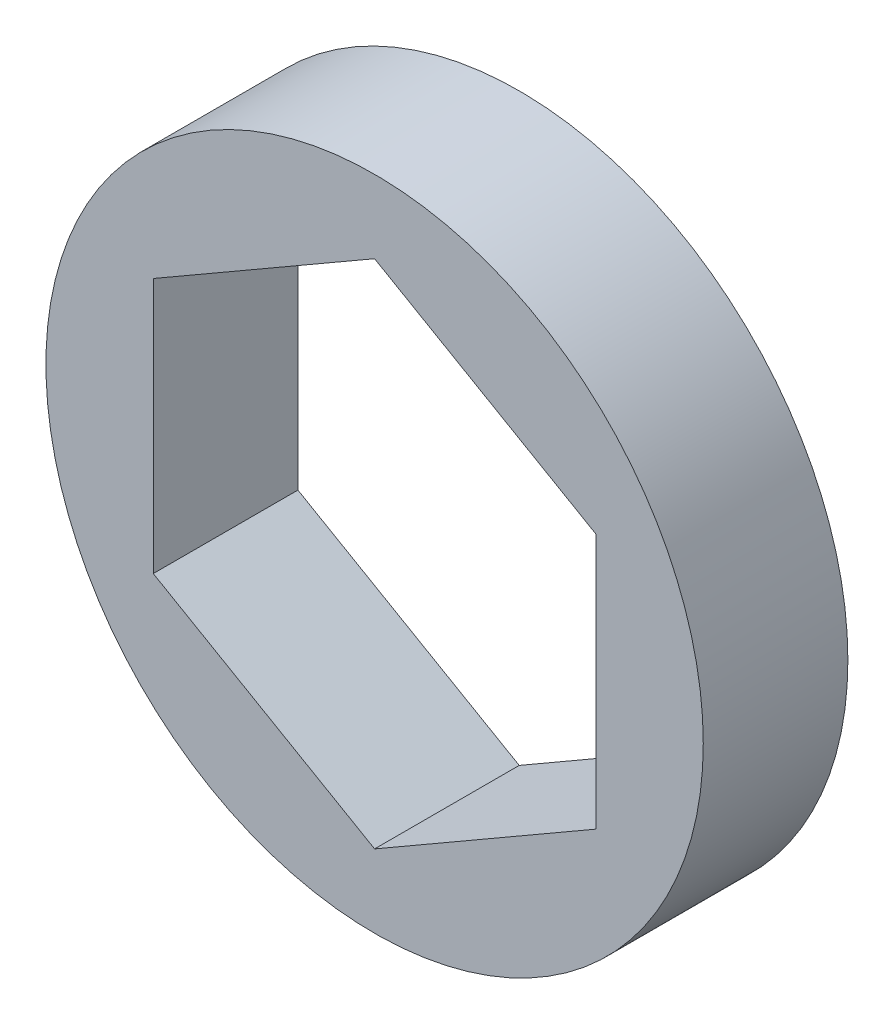
SolidWorks part; units mm, degrees
material "PET"
ref_plane "Front Plane" through (0, 0, 0) normal (0, 0, 1) x (1, 0, 0)
ref_plane "Top Plane" through (0, 0, 0) normal (0, 1, 0) x (1, 0, 0)
ref_plane "Right Plane" through (0, 0, 0) normal (1, 0, 0) x (0, 0, -1)
sketch "Sketch2" plane through (0, 0, 0) normal (0, 0, 1) x (1, 0, 0)
  line L1 (6.4135, 3.7028) -> (0, 7.4057)
  line L2 (0, 7.4057) -> (-6.4135, 3.7028)
  line L3 (-6.4135, 3.7028) -> (-6.4135, -3.7028)
  line L4 (-6.4135, -3.7028) -> (0, -7.4057)
  line L5 (0, -7.4057) -> (6.4135, -3.7028)
  line L6 (6.4135, -3.7028) -> (6.4135, 3.7028)
  circle A0 centre (0, 0) radius 9.525
  circle A1 centre (0, 0) radius 6.4135 construction
  dimension "D1" = 12.827
  dimension "D2" = 19.05
extrude "Boss-Extrude1" add sketch "Sketch2" along normal blind 4.191
